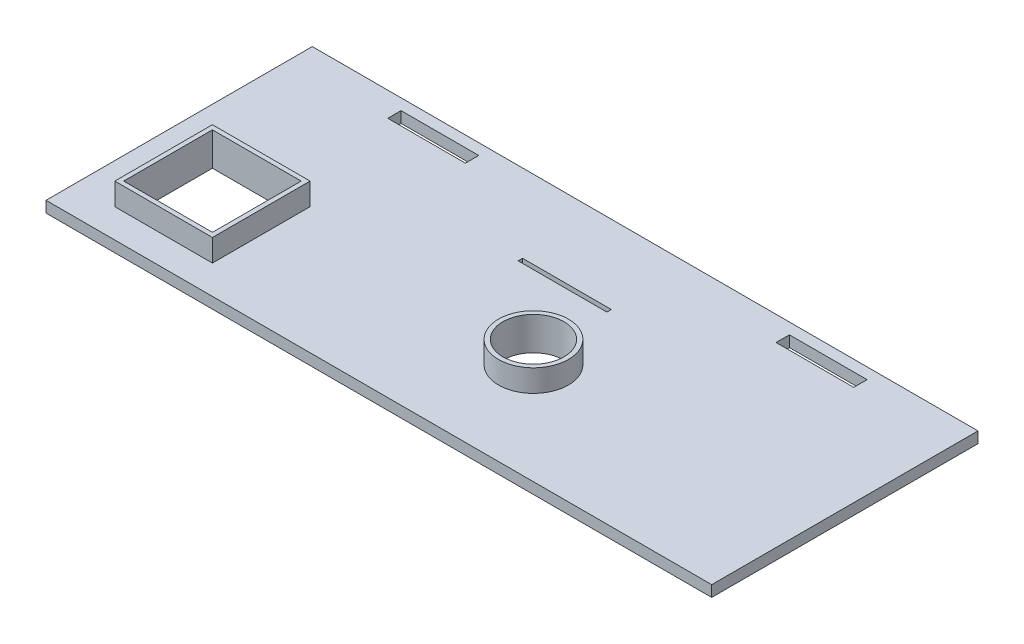
SolidWorks part; units mm, degrees
ref_plane "Front" through (0, 0, 0) normal (0, 0, 1) x (1, 0, 0)
ref_plane "Top" through (0, 0, 0) normal (0, 1, 0) x (1, 0, 0)
ref_plane "Right" through (0, 0, 0) normal (1, 0, 0) x (0, 0, -1)
sketch "Sketch1" plane through (0, 0, 0) normal (0, 1, 0) x (1, 0, 0)
  line L1 (150, 60) -> (-150, 60)
  line L2 (150, 60) -> (150, -60)
  line L3 (150, -60) -> (-150, -60)
  line L4 (-150, 60) -> (-150, -60)
  line L5 (0, -60) -> (0, 60) construction
  line L6 (150, 0) -> (-150, 0) construction
  line L7 (-70, 55) -> (-105, 55)
  line L8 (-70, 55) -> (-70, 49)
  line L9 (-70, 49) -> (-105, 49)
  line L10 (-105, 55) -> (-105, 49)
  line L11 (-87.5, 49) -> (-87.5, 55) construction
  line L12 (-70, 52) -> (-105, 52) construction
  line L13 (105, 55) -> (70, 55)
  line L14 (105, 55) -> (105, 49)
  line L15 (105, 49) -> (70, 49)
  line L16 (70, 55) -> (70, 49)
  line L17 (87.5, 49) -> (87.5, 55) construction
  line L18 (105, 52) -> (70, 52) construction
  line L19 (-90, -5) -> (-130, -5)
  line L20 (-90, -5) -> (-90, -45)
  line L21 (-90, -45) -> (-130, -45)
  line L22 (-130, -5) -> (-130, -45)
  line L23 (-110, -45) -> (-110, -5) construction
  line L24 (-90, -25) -> (-130, -25) construction
  line L25 (20, 22.7568) -> (-20, 22.7568)
  line L26 (20, 22.7568) -> (20, 24.7568)
  line L27 (20, 24.7568) -> (-20, 24.7568)
  line L28 (-20, 22.7568) -> (-20, 24.7568)
  line L29 (0, 24.7568) -> (0, 22.7568) construction
  line L30 (20, 23.7568) -> (-20, 23.7568) construction
  circle A0 centre (24.0744, -14.4073) radius 13.75
  point P0 (0, 0)
  point P4 (-87.5, 52)
  point P8 (87.5, 52)
  point P12 (0, 23.7568)
  point P13 (-110, -25)
  dimension "D13" = 27.5
  dimension "D1" = 35
  dimension "D2" = 6
  dimension "D3" = 5
  dimension "D4" = 120
  dimension "D5" = 300
  dimension "D6" = 140
  dimension "D7" = 70
  dimension "D8" = 40
  dimension "D9" = 40
  dimension "D10" = 20
  dimension "D11" = 2
  dimension "D12" = 40
  dimension "D14" = 15
extrude "Boss-Extrude1" add sketch "Sketch1" along normal blind 5
sketch "Sketch3" plane through (0, 5, 0) normal (0, 1, 0) x (1, 0, 0)
  line L0 (-130, -45) -> (-90, -45) construction
  line L1 (-130, -5) -> (-130, -45) construction
  line L2 (-90, -5) -> (-130, -5) construction
  line L3 (-90, -45) -> (-90, -5) construction
  line L4 (-130, -45) -> (-90, -45)
  line L5 (-130, -5) -> (-130, -45)
  line L6 (-90, -5) -> (-130, -5)
  line L7 (-90, -45) -> (-90, -5)
  line L8 (-88, -3) -> (-132, -3)
  line L9 (-132, -3) -> (-132, -47)
  line L10 (-132, -47) -> (-88, -47)
  line L11 (-88, -47) -> (-88, -3)
  circle A0 centre (24.0744, -14.4073) radius 13.75 construction
  circle A1 centre (24.0744, -14.4073) radius 13.75
  circle A2 centre (24.0744, -14.4073) radius 15.75
  dimension "D1" = 2
extrude "Boss-Extrude5" add sketch "Sketch3" along normal blind 10 contours L8 L9 L10 L11 | L4 L7 L6 L5 | A2 | A1
